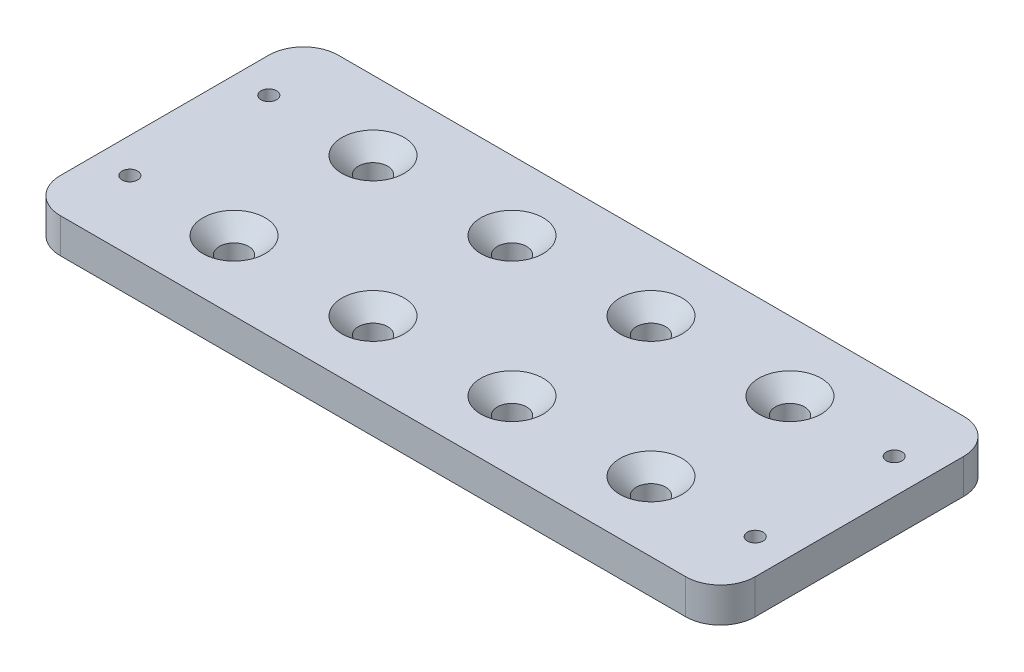
SolidWorks part; units mm, degrees
ref_plane "Front Plane" through (0, 0, 0) normal (0, 0, 1) x (1, 0, 0)
ref_plane "Top Plane" through (0, 0, 0) normal (0, 1, 0) x (1, 0, 0)
ref_plane "Right Plane" through (0, 0, 0) normal (1, 0, 0) x (0, 0, -1)
sketch "Sketch1" plane through (0, 0, 0) normal (0, 1, 0) x (1, 0, 0)
  line L1 (-100, -40) -> (100, -40)
  line L2 (-100, -40) -> (-100, 40)
  line L3 (-100, 40) -> (100, 40)
  line L4 (100, -40) -> (100, 40)
  line L5 (-100, -40) -> (100, 40) construction
  line L6 (-100, 40) -> (100, -40) construction
  point P0 (0, 0)
  dimension "D1" = 200
  dimension "D2" = 80
extrude "Boss-Extrude1" add sketch "Sketch1" along normal blind 10
sketch "Sketch2" plane through (0, 10, 0) normal (0, 1, 0) x (1, 0, 0)
  line L1 (-100, -40) -> (100, -40) construction
  line L2 (0, 40) -> (0, -40) construction
  line L4 (-100, 40) -> (100, 40) construction
  point P0 (-20, 20)
  point P1 (20, -20)
  point P5 (60, -20)
  point P6 (-20, -20)
  point P7 (-60, -20)
  point P8 (60, 20)
  point P9 (20, 20)
  point P24 (-60, 20)
  dimension "D1" = 60
  dimension "D4" = 2
  dimension "D6" = 80
  dimension "D2" = 20
  dimension "D3" = 2
hole_wizard "CSK for M8 SFHCS1" positions "Sketch2" profile "Sketch3" countersink size "M8" standard "ANSI Metric" end condition through all
sketch "Sketch3" plane through (-20, 10, -20) normal (1, 0, 0) x (0, 0, 1)
  line L0 (0, 0) -> (0, 10)
  line L1 (0, 10) -> (4.2, 10)
  line L2 (4.2, 10) -> (4.2, 4.76)
  line L3 (4.2, 4.76) -> (8.96, 0)
  line L5 (8.96, 0) -> (0, 0)
  line L6 (-4.2, 4.76) -> (-8.96, 0) construction
  line L11 (0, -6.35) -> (0, 107.95) construction
  dimension "Thru Hole Dia." = 8.4
  dimension "Thru Hole Depth" = 10
  dimension "Near C'Sink Dia." = 17.92
  dimension "Near C'Sink Angle" = 90
sketch "Sketch4" plane through (0, 10, 0) normal (0, 1, 0) x (1, 0, 0)
  line L0 (-100, -40) -> (-100, 40) construction
  line L1 (-100, 40) -> (100, 40) construction
  circle A0 centre (-20, 20) radius 8.96 construction
  point P0 (-90, 20)
  point P8 (90, 20)
  point P9 (90, -20)
  point P10 (-90, -20)
  dimension "D1" = 10
  dimension "D2" = 20
  dimension "D5" = 110
  dimension "D6" = 40
  dimension "D3" = 2
  dimension "D4" = 2
hole_wizard "M4 Clearance Hole1" positions "Sketch4" profile "Sketch5" hole size "M4" standard "ANSI Metric" end condition through all
sketch "Sketch5" plane through (-90, 10, -20) normal (1, 0, 0) x (0, 0, 1)
  line L0 (0, 0) -> (0, 10)
  line L1 (0, 10) -> (2.25, 10)
  line L2 (2.25, 10) -> (2.25, 0)
  line L5 (2.25, 0) -> (0, 0)
  line L11 (0, -6.35) -> (0, 107.95) construction
  dimension "Thru Hole Dia." = 4.5
  dimension "Thru Hole Depth" = 10
fillet "Fillet1" radius 10 4 edges at (-100, 5, -40) (-100, 5, 40) (100, 5, -40) (100, 5, 40)
